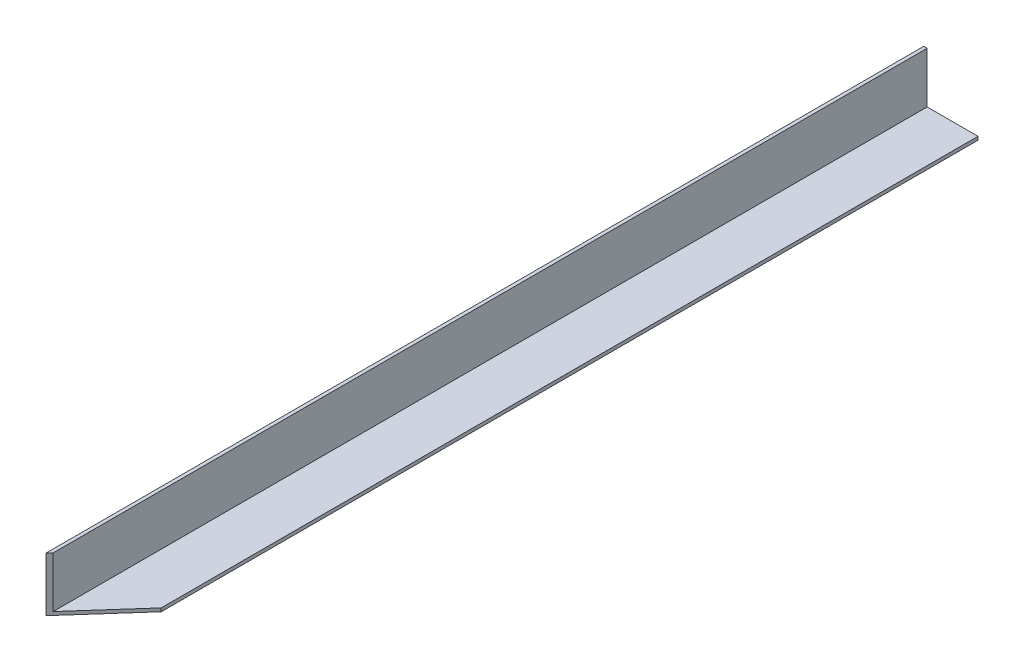
SolidWorks part; units mm, degrees
ref_plane "Front Plane" through (0, 0, 0) normal (0, 0, 1) x (1, 0, 0)
ref_plane "Top Plane" through (0, 0, 0) normal (0, 1, 0) x (1, 0, 0)
ref_plane "Right Plane" through (0, 0, 0) normal (1, 0, 0) x (0, 0, -1)
sketch "Sketch1" plane through (0, 0, 0) normal (0, 0, 1) x (1, 0, 0)
  line L0 (0, 0) -> (0, 15)
  line L1 (0, 0) -> (15, 0)
extrude "Extrude-Thin1" add sketch "Sketch1" along normal blind 259 thin thin type one direction wall 1
sketch "Sketch2" plane through (0, -1, 0) normal (0, -1, 0) x (-1, 0, 0)
  line L0 (1, -259) -> (-15, -241)
  line L1 (-15, -259) -> (-15, 0) construction
  line L2 (-15, -241) -> (-15, -259)
  line L3 (-15, -259) -> (1, -259)
extrude "Cut-Extrude1" cut sketch "Sketch2" against normal through all
